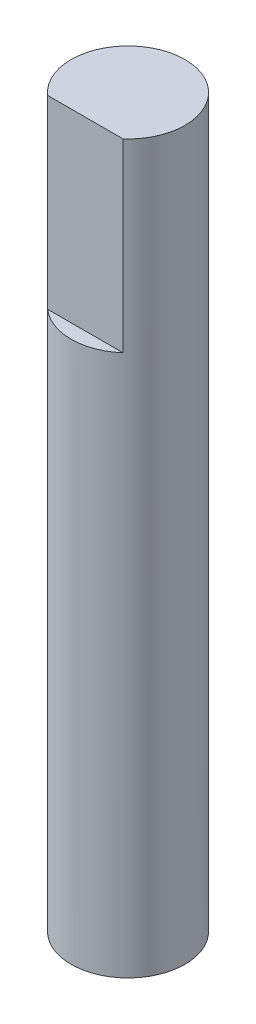
SolidWorks part; units mm, degrees
ref_plane "Front Plane" through (0, 0, 0) normal (0, 0, 1) x (1, 0, 0)
ref_plane "Top Plane" through (0, 0, 0) normal (0, 1, 0) x (1, 0, 0)
ref_plane "Right Plane" through (0, 0, 0) normal (1, 0, 0) x (0, 0, -1)
sketch "Sketch1" plane through (0, 0, 0) normal (0, 1, 0) x (1, 0, 0)
  line L0 (0, -4) -> (0, -3) construction
  line L1 (-2.6458, -3) -> (2.6458, -3)
  circle A0 centre (0, 0) radius 4 construction
  arc A1 (-2.6458, -3) -> (2.6458, -3) centre (0, 0) cw
  point P7 (0, -3)
  dimension "D1" = 8
  dimension "D2" = 1
extrude "Boss-Extrude1" add sketch "Sketch1" along normal blind 13
sketch "Sketch2" plane through (0, 0, 0) normal (0, -1, 0) x (1, 0, 0)
  circle A0 centre (0, 0) radius 4
  dimension "D1" = 8
extrude "Boss-Extrude2" add sketch "Sketch2" along normal blind 38
